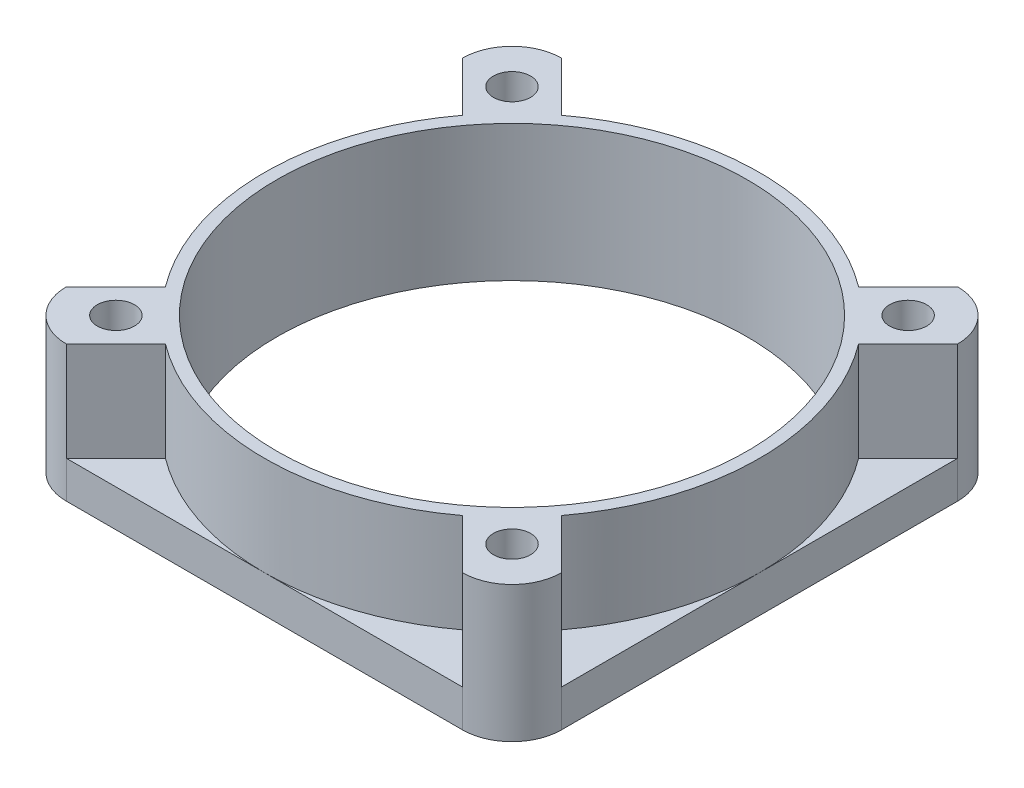
SolidWorks part; units mm, degrees
ref_plane "Front Plane" through (0, 0, 0) normal (0, 0, 1) x (1, 0, 0)
ref_plane "Top Plane" through (0, 0, 0) normal (0, 1, 0) x (1, 0, 0)
ref_plane "Right Plane" through (0, 0, 0) normal (1, 0, 0) x (0, 0, -1)
sketch "Sketch1" plane through (0, 0, 0) normal (0, 1, 0) x (1, 0, 0)
  line L1 (0, 0) -> (40, 0)
  line L2 (0, 0) -> (0, 40)
  line L3 (0, 40) -> (40, 40)
  line L4 (40, 0) -> (40, 40)
  dimension "D1" = 40
  dimension "D2" = 40
extrude "Boss-Extrude1" add sketch "Sketch1" along normal blind 11
fillet "Fillet1" radius 4 1 edges at (40, 5.5, 0)
fillet "Fillet2" radius 4 1 edges at (0, 5.5, 0)
fillet "Fillet3" radius 4 1 edges at (0, 5.5, -40)
fillet "Fillet4" radius 4 1 edges at (40, 5.5, -40)
sketch "Sketch2" plane through (0, 11, 0) normal (0, 1, 0) x (1, 0, 0)
  circle A0 centre (20, 20) radius 19
  dimension "D1" = 38
extrude "Cut-Extrude1" cut sketch "Sketch2" against normal blind 11
sketch "Sketch3" plane through (0, 11, 0) normal (0, 1, 0) x (1, 0, 0)
  line L0 (20, 20) -> (42.8742, 42.8742) construction
  line L1 (20, 20) -> (43.9465, -3.9465) construction
  line L2 (20, 20) -> (-2.8296, -2.8296) construction
  line L3 (20, 20) -> (-1.9145, 41.9145) construction
  line L4 (0, 36) -> (4, 32)
  line L5 (4, 40) -> (8, 36)
  line L6 (36, 40) -> (32, 36)
  line L7 (40, 36) -> (36, 32)
  line L8 (40, 4) -> (36, 8)
  line L9 (36, 0) -> (32, 4)
  line L10 (4, 0) -> (8, 4)
  line L11 (0, 4) -> (4, 8)
  circle A0 centre (20, 20) radius 20
  line M2 (40, 4) -> (40, 36)
  line M4 (36, 40) -> (4, 40)
  line M6 (0, 36) -> (0, 4)
  line M8 (4, 0) -> (36, 0)
extrude "Cut-Extrude2" cut sketch "Sketch3" against normal blind 8 contours A0 L4 M6 | A0 L5 M4 | A0 L6 M4 | A0 L7 M2 | A0 L8 M2 | A0 L9 M8 | A0 L10 M8 | A0 L11 M6
sketch "Sketch4" plane through (0, 11, 0) normal (0, 1, 0) x (1, 0, 0)
  circle A0 centre (36, 36) radius 1.5
  circle A1 centre (4, 36) radius 1.5
  circle A2 centre (4, 4) radius 1.5
  circle A3 centre (36, 4) radius 1.5
  dimension "D1" = 3
  dimension "D2" = 3
  dimension "D4" = 3
  dimension "D3" = 3
extrude "Cut-Extrude3" cut sketch "Sketch4" against normal blind 11
